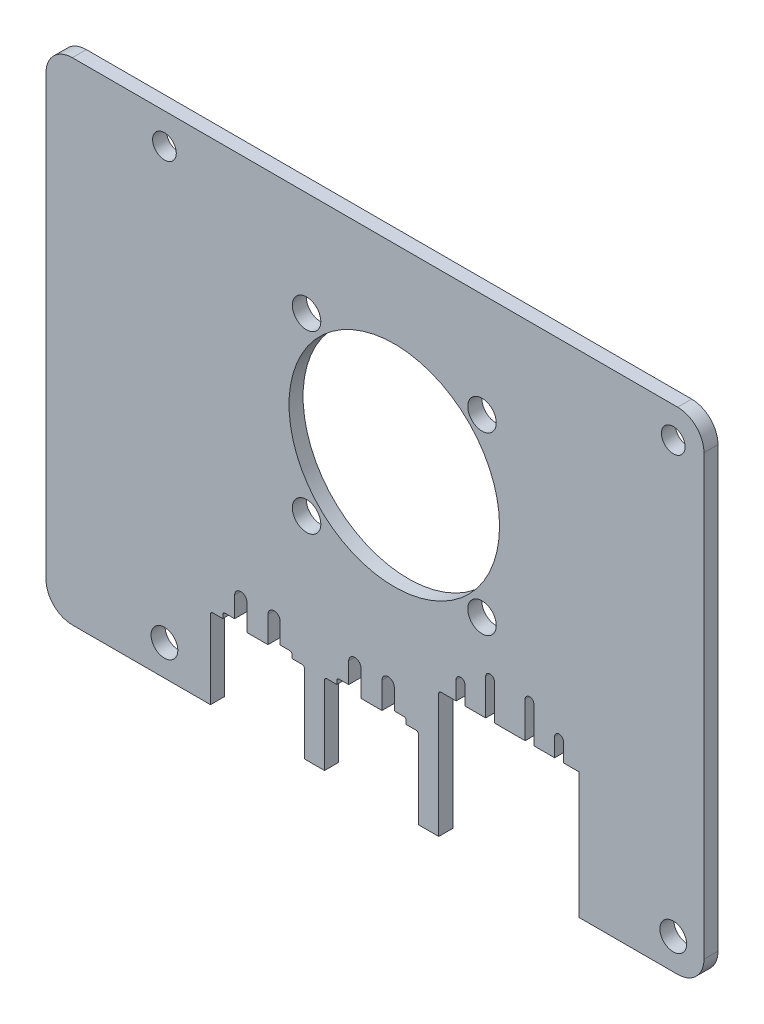
SolidWorks part; units mm, degrees
ref_plane "Front Plane" through (0, 0, 0) normal (0, 0, 1) x (1, 0, 0)
ref_plane "Top Plane" through (0, 0, 0) normal (0, 1, 0) x (1, 0, 0)
ref_plane "Right Plane" through (0, 0, 0) normal (1, 0, 0) x (0, 0, -1)
sketch "Sketch1" plane through (0, 0, 0) normal (0, 0, 1) x (1, 0, 0)
  line L0 (22.5, 25) -> (22.5, -25)
  line L1 (19, 24.5) -> (19.5, 25) construction
  line L2 (39.5, 28) -> (-39.5, 28) construction
  line L4 (42.5, -25) -> (42.5, 25)
  line L5 (39.5, 28) -> (-39.5, 28)
  line L6 (-42.5, 25) -> (-42.5, -25)
  line L7 (-39.5, -28) -> (39.5, -28)
  line L9 (19.5, 28) -> (-39.5, 28)
  line L10 (-42.5, 25) -> (-42.5, -25)
  line L11 (-39.5, -28) -> (19.5, -28)
  arc A0 (22.5, 25) -> (19.5, 28) centre (19.5, 25) ccw
  arc A1 (22.5, -25) -> (19.5, -28) centre (19.5, -25) cw
  circle A2 centre (19, 24.5) radius 1.35 construction
  circle A3 centre (-39, 24.5) radius 1.35 construction
  arc A4 (42.5, 25) -> (39.5, 28) centre (39.5, 25) ccw
  arc A5 (-39.5, 28) -> (-42.5, 25) centre (-39.5, 25) ccw
  arc A6 (-42.5, -25) -> (-39.5, -28) centre (-39.5, -25) ccw
  arc A7 (39.5, -28) -> (42.5, -25) centre (39.5, -25) ccw
  arc A9 (-39.5, 28) -> (-42.5, 25) centre (-39.5, 25) ccw
  arc A10 (-42.5, -25) -> (-39.5, -28) centre (-39.5, -25) ccw
  circle A11 centre (-39, -24.5) radius 1.524 construction
  circle A12 centre (19, -24.5) radius 1.524 construction
  circle A13 centre (-39, 24.5) radius 1.35
  circle A14 centre (-39, -24.5) radius 1.524
  circle A15 centre (19, -24.5) radius 1.524
  circle A16 centre (19, 24.5) radius 1.35
  point P18 (19, 24.5)
  dimension "D2" = 45
  dimension "D1" = 0
extrude "Boss-Extrude1" add sketch "Sketch1" along normal mid plane 1.6
sketch "Sketch2" plane through (0, 0, 0.8) normal (0, 0, 1) x (1, 0, 0)
  circle A0 centre (-2.7999, 16.11) radius 1.625
  circle A1 centre (-22.7999, 16.11) radius 1.625
  circle A2 centre (-22.7999, -3.89) radius 1.625
  circle A3 centre (-2.7999, -3.89) radius 1.625
  circle A4 centre (-12.7999, 6.11) radius 12
  point P15 (0, 0)
  dimension "D1" = 3.25
  dimension "D2" = 24
extrude "Cut-Extrude1" cut sketch "Sketch2" against normal through all
sketch "Sketch3" plane through (0, 0, 0.8) normal (0, 0, 1) x (1, 0, 0)
  line L4 (-42.5, 25) -> (-42.5, -25)
  line L5 (-39.5, -28) -> (19.5, -28)
  line L6 (22.5, -25) -> (22.5, 25)
  line L7 (19.5, 28) -> (-39.5, 28)
  line L8 (-42.5, 25) -> (-42.5, -25)
  line L9 (-39.5, -28) -> (19.5, -28)
  line L10 (22.5, -25) -> (22.5, 25)
  line L11 (19.5, 28) -> (-39.5, 28)
  arc A4 (-39.5, 28) -> (-42.5, 25) centre (-39.5, 25) ccw
  arc A5 (-42.5, -25) -> (-39.5, -28) centre (-39.5, -25) ccw
  arc A6 (19.5, -28) -> (22.5, -25) centre (19.5, -25) ccw
  arc A7 (22.5, 25) -> (19.5, 28) centre (19.5, 25) ccw
  arc A8 (-39.5, 28) -> (-42.5, 25) centre (-39.5, 25) ccw
  arc A9 (-42.5, -25) -> (-39.5, -28) centre (-39.5, -25) ccw
  arc A10 (19.5, -28) -> (22.5, -25) centre (19.5, -25) ccw
  arc A11 (22.5, 25) -> (19.5, 28) centre (19.5, 25) ccw
  point P0 (14.18, 25.89)
  point P2 (-12.7999, 6.11)
  point P7 (19, -24.5)
  point P12 (19, 24.5)
  point P15 (-39, 24.5)
  point P17 (-39, -24.5)
  point P18 (0, 0)
  point P20 (0, 0)
  point P21 (0, 0)
  point P28 (0, 0)
  point P29 (-14.5946, 28)
  dimension "D5" = 35.2999
  dimension "D2" = 3
  dimension "D3" = 59
  dimension "D4" = 53
  dimension "D6" = 34.11
  dimension "D7" = 53.89
  dimension "D8" = 8.32
  dimension "D1" = 0
sketch "Sketch4" plane through (0, 0, 0.8) normal (0, 0, 1) x (1, 0, 0)
  line L1 (-49.5, 28) -> (-39.5, 28)
  line L2 (-52.5, 25) -> (-52.5, -25)
  line L3 (-49.5, -28) -> (-39.5, -28)
  line L4 (-39.5, 28) -> (-39.5, -28)
  line L5 (-52.5, 28) -> (-39.5, -28) construction
  line L6 (-52.5, -28) -> (-39.5, 28) construction
  line L8 (19.5, 28) -> (-39.5, 28) construction
  arc A0 (-52.5, -25) -> (-49.5, -28) centre (-49.5, -25) ccw
  arc A1 (-49.5, 28) -> (-52.5, 25) centre (-49.5, 25) ccw
  arc A2 (-39.5, 28) -> (-42.5, 25) centre (-39.5, 25) ccw construction
  point P0 (-46, 0)
  point P5 (-39.5, 28)
  point P13 (0, 0)
  point P16 (-42.5, 17.6848)
  arc M14 (-39.5, 28) -> (-42.5, 25) centre (-39.5, 25) ccw
  line M15 (-42.5, 25) -> (-42.5, -25)
  arc M16 (-42.5, -25) -> (-39.5, -28) centre (-39.5, -25) ccw
  dimension "D3" = 13
extrude "Boss-Extrude2" add sketch "Sketch4" against normal up to surface (1.6 mm away) contours L1 A1 L2 A0 L3 M16 M15 M14 up to face at (-21.1749, 16.11, -0.8)
sketch "Sketch5" plane through (0, 0, 0.8) normal (0, 0, 1) x (1, 0, 0)
  line L0 (-49.5, -28) -> (19.5, -28) construction
  line L1 (-33.5, -18.8) -> (-23.3, -18.8)
  line L2 (-33.75, -19.05) -> (-33.75, -28)
  line L3 (-33.75, -28) -> (-23.05, -28)
  line L4 (-23.05, -19.05) -> (-23.05, -28)
  line L5 (-33.75, -18.8) -> (-23.05, -28) construction
  line L6 (-33.75, -28) -> (-23.05, -18.8) construction
  line L7 (-30.9, -19.8) -> (-25.9, -19.8) construction
  line L12 (-20.5, -18.8) -> (-11.925, -18.8) construction
  line L13 (-10.05, -28) -> (-20.75, -28)
  line L14 (8.4675, -28) -> (-7.7325, -28)
  line L15 (8.4675, -28) -> (8.4675, -13.875)
  line L16 (8.2175, -13.625) -> (-7.4825, -13.625)
  line L17 (-7.7325, -28) -> (-7.7325, -13.875)
  line L18 (8.4675, -28) -> (-7.7325, -13.625) construction
  line L19 (8.4675, -13.625) -> (-7.7325, -28) construction
  line L20 (-29.7, -19.8) -> (-32.1, -19.8) construction
  line L21 (-24.7, -19.8) -> (-27.1, -19.8) construction
  line L22 (-33.5, -29.5) -> (-33.5, -18.8) construction
  line L23 (-0.1325, -19) -> (0.8675, -19) construction
  line L24 (-33.5, -18.8) -> (-24.925, -18.8) construction
  line L25 (-10.05, -28) -> (-10.05, -19.05)
  line L26 (-10.3, -18.8) -> (-20.5, -18.8)
  line L27 (-20.75, -28) -> (-20.75, -19.05)
  line L28 (-10.05, -28) -> (-20.75, -18.8) construction
  line L29 (-10.05, -18.8) -> (-20.75, -28) construction
  line L30 (-30.3, -18.8) -> (-30.3, -15.8) construction
  line L31 (-31, -18.8) -> (-31, -15.8)
  line L32 (-29.6, -18.8) -> (-29.6, -15.8)
  line L33 (-29.7, -15.8) -> (-30.9, -15.8) construction
  line L34 (-29.7, -15.8) -> (-30.9, -15.8)
  line L35 (-31, -18.14) -> (-32.1, -18.14)
  line L36 (-32.35, -18.39) -> (-32.35, -18.8)
  line L37 (-30.9, -18.14) -> (-32.1, -18.14) construction
  line L38 (-30.9, -18.14) -> (-32.1, -18.14)
  line L39 (-28.4, -19.8) -> (-28.4, -23.4) construction
  line L40 (-26.5, -18.8) -> (-26.5, -15.8) construction
  line L41 (-25.8, -18.8) -> (-25.8, -15.8)
  line L42 (-27.2, -18.8) -> (-27.2, -15.8)
  line L43 (-24.45, -18.39) -> (-24.45, -18.8)
  line L44 (-25.8, -18.14) -> (-24.7, -18.14)
  line L45 (-19.35, -18.39) -> (-19.35, -18.8)
  line L46 (-18, -18.14) -> (-19.1, -18.14)
  line L47 (-12.8, -18.14) -> (-11.7, -18.14)
  line L48 (-11.45, -18.39) -> (-11.45, -18.8)
  line L49 (-17.3, -18.8) -> (-17.3, -15.8) construction
  line L50 (-18, -18.8) -> (-18, -15.8)
  line L51 (-16.6, -18.8) -> (-16.6, -15.8)
  line L52 (-13.5, -18.8) -> (-13.5, -15.8) construction
  line L53 (-12.8, -18.8) -> (-12.8, -15.8)
  line L54 (-14.2, -18.8) -> (-14.2, -15.8)
  line L55 (8.235, -29.25) -> (8.235, -13.625) construction
  line L56 (8.235, -13.625) -> (-4.3964, -13.625) construction
  line L57 (-7.4268, -29.25) -> (-7.4268, -13.875) construction
  line L58 (8.235, -29.25) -> (8.235, -13.625)
  line L59 (8.235, -13.625) -> (-4.3964, -13.625)
  line L60 (-7.4268, -29.25) -> (-7.4268, -13.875)
  line L61 (-5.2475, -13.625) -> (-5.2475, -11.525) construction
  line L62 (-5.7475, -13.625) -> (-5.7475, -11.525)
  line L63 (-4.7475, -13.625) -> (-4.7475, -11.525)
  line L64 (-1.8825, -13.625) -> (-1.8825, -9.525) construction
  line L65 (-2.3825, -13.625) -> (-2.3825, -9.525)
  line L66 (-1.3825, -13.625) -> (-1.3825, -9.525)
  line L67 (0.3675, -20.8125) -> (0.3675, -13.625) construction
  line L68 (5.9825, -13.625) -> (5.9825, -11.525) construction
  line L69 (6.4825, -13.625) -> (6.4825, -11.525)
  line L70 (5.4825, -13.625) -> (5.4825, -11.525)
  line L71 (2.6175, -13.625) -> (2.6175, -9.525) construction
  line L72 (3.1175, -13.625) -> (3.1175, -9.525)
  line L73 (2.1175, -13.625) -> (2.1175, -9.525)
  line L75 (-2.3825, -11.575) -> (-4.7475, -11.575) construction
  line L76 (-5.398, -11.623) -> (-5.398, -20)
  line L77 (-1.734, -20) -> (-1.734, -9.623)
  line L78 (-1.734, -20) -> (-1.734, -9.623)
  line L79 (-5.398, -11.623) -> (-5.398, -20)
  line L82 (-33.75, -28) -> (-33.75, -29.5)
  line L83 (-33.5, -29.75) -> (-23.3, -29.75)
  line L84 (-23.05, -29.5) -> (-23.05, -28)
  line L85 (-33.5, -29.5) -> (-24.925, -29.5) construction
  line L86 (-20.75, -28) -> (-20.75, -28.2)
  line L87 (-20.5, -28.45) -> (-10.3, -28.45)
  line L88 (-10.05, -28.2) -> (-10.05, -28)
  line L89 (-14.8861, -28.2) -> (-12.9, -28.2) construction
  line L90 (-7.7325, -28) -> (-7.7325, -29.5)
  line L91 (-7.4825, -29.75) -> (8.2175, -29.75)
  line L92 (8.4675, -29.5) -> (8.4675, -28)
  line L94 (-0.1325, -19) -> (0.8675, -19)
  arc A0 (-31, -18.8) -> (-29.6, -18.8) centre (-30.3, -18.8) ccw
  arc A1 (-29.6, -15.8) -> (-31, -15.8) centre (-30.3, -15.8) ccw
  arc A2 (-32.35, -18.39) -> (-32.1, -18.14) centre (-32.1, -18.39) cw
  arc A3 (-25.8, -18.8) -> (-27.2, -18.8) centre (-26.5, -18.8) cw
  arc A4 (-27.2, -15.8) -> (-25.8, -15.8) centre (-26.5, -15.8) cw
  arc A5 (-24.45, -18.39) -> (-24.7, -18.14) centre (-24.7, -18.39) ccw
  arc A6 (-10.05, -19.05) -> (-10.3, -18.8) centre (-10.3, -19.05) ccw
  arc A7 (-20.5, -18.8) -> (-20.75, -19.05) centre (-20.5, -19.05) ccw
  arc A8 (-23.3, -18.8) -> (-23.05, -19.05) centre (-23.3, -19.05) cw
  arc A9 (-33.5, -18.8) -> (-33.75, -19.05) centre (-33.5, -19.05) ccw
  arc A10 (-19.35, -18.39) -> (-19.1, -18.14) centre (-19.1, -18.39) cw
  arc A11 (-11.45, -18.39) -> (-11.7, -18.14) centre (-11.7, -18.39) ccw
  arc A12 (-18, -18.8) -> (-16.6, -18.8) centre (-17.3, -18.8) ccw
  arc A13 (-16.6, -15.8) -> (-18, -15.8) centre (-17.3, -15.8) ccw
  arc A14 (-12.8, -18.8) -> (-14.2, -18.8) centre (-13.5, -18.8) cw
  arc A15 (-14.2, -15.8) -> (-12.8, -15.8) centre (-13.5, -15.8) cw
  arc A16 (-5.7475, -13.625) -> (-4.7475, -13.625) centre (-5.2475, -13.625) ccw
  arc A17 (-4.7475, -11.525) -> (-5.7475, -11.525) centre (-5.2475, -11.525) ccw
  arc A18 (-2.3825, -13.625) -> (-1.3825, -13.625) centre (-1.8825, -13.625) ccw
  arc A19 (-1.3825, -9.525) -> (-2.3825, -9.525) centre (-1.8825, -9.525) ccw
  arc A20 (6.4825, -13.625) -> (5.4825, -13.625) centre (5.9825, -13.625) cw
  arc A21 (5.4825, -11.525) -> (6.4825, -11.525) centre (5.9825, -11.525) cw
  arc A22 (3.1175, -13.625) -> (2.1175, -13.625) centre (2.6175, -13.625) cw
  arc A23 (2.1175, -9.525) -> (3.1175, -9.525) centre (2.6175, -9.525) cw
  arc A24 (8.4675, -13.875) -> (8.2175, -13.625) centre (8.2175, -13.875) ccw
  arc A25 (-7.4825, -13.625) -> (-7.7325, -13.875) centre (-7.4825, -13.875) ccw
  arc A26 (-23.3, -29.75) -> (-23.05, -29.5) centre (-23.3, -29.5) ccw
  arc A27 (-33.75, -29.5) -> (-33.5, -29.75) centre (-33.5, -29.5) ccw
  arc A28 (-10.3, -28.45) -> (-10.05, -28.2) centre (-10.3, -28.2) ccw
  arc A29 (-20.75, -28.2) -> (-20.5, -28.45) centre (-20.5, -28.2) ccw
  arc A30 (8.2175, -29.75) -> (8.4675, -29.5) centre (8.2175, -29.5) ccw
  arc A31 (-7.7325, -29.5) -> (-7.4825, -29.75) centre (-7.4825, -29.5) ccw
  point P0 (-28.4, -23.4)
  point P8 (0.3675, -20.8125)
  point P9 (-15.4, -23.4)
  point P21 (-28.4, -19.8)
  point P32 (-30.3, -17.3)
  point P49 (-26.5, -17.3)
  point P71 (-5.2475, -12.575)
  point P75 (-17.3, -17.3)
  point P87 (-13.5, -17.3)
  point P107 (-1.8825, -11.575)
  point P118 (5.9825, -12.575)
  point P125 (2.6175, -11.575)
  point P136 (-3.565, -11.575)
  point P171 (0.3675, -19)
  dimension "D5" = 0.25
  dimension "D6" = 0.25
  dimension "D11" = 0.5
  dimension "D14" = 0.25
  dimension "D15" = 0.25
  dimension "D18" = 0.25
  dimension "D19" = 0.25
  dimension "D1" = 0.25
  dimension "D2" = 13
  dimension "D3" = 0.1
  dimension "D4" = 0.1
  dimension "D8" = 13
  dimension "D9" = 16.2
  dimension "D10" = 16.125
  dimension "D12" = 2.25
  dimension "D13" = 5.615
  dimension "D16" = 0.25
  dimension "D17" = 0.25
  dimension "D20" = 2.1
  dimension "D21" = 10.95
  dimension "D22" = 7.9
  dimension "D23" = 5.2
  dimension "D24" = 2.4
  dimension "D25" = 9.65
  dimension "D26" = 4.1
  dimension "D27" = 6.115
  dimension "D28" = 5.615
  dimension "D29" = 2.25
  dimension "D30" = 2.365
  dimension "D31" = 5.115
  dimension "D32" = 2.75
  dimension "D33" = 3.9325
  dimension "D7" = 2
extrude "Cut-Extrude2" cut sketch "Sketch5" against normal through all
sketch "Sketch6" plane through (0, 0, 0.8) normal (0, 0, 1) x (1, 0, 0)
  line L0 (2.1175, -13.625) -> (-1.3825, -13.625) construction
  line L1 (-14.2, -18.8) -> (-16.6, -18.8) construction
  line L2 (-29.6, -18.8) -> (-27.2, -18.8) construction
  line L3 (22.5, -25) -> (22.5, 25) construction
  line L4 (19.5, 28) -> (-49.5, 28) construction
  line L5 (8.235, -28) -> (19.5, -28) construction
  line L6 (-52.5, 25) -> (-52.5, -25) construction
  line L7 (-52.5, 25) -> (-52.5, -25)
  line L8 (22.5, -25) -> (22.5, 25)
  line L9 (-47.5024, 3.9375) -> (-47.5024, -3.9295) construction
  line L10 (-49.5, -28) -> (-33.75, -28) construction
  point P0 (0.3675, -13.625)
  point P1 (-15.4, -18.8)
  point P4 (-28.4, -18.8)
  point P21 (-47.5024, 0.004)
  point P24 (0, 0)
  dimension "D1" = 22.1325
  dimension "D2" = 37.9
  dimension "D3" = 50.9
  dimension "D4" = 41.625
  dimension "D5" = 46.8
  dimension "D6" = 9.2
  dimension "D7" = 14.375
  dimension "D8" = 75
  dimension "D9" = 70.0024
  dimension "D10" = 28.004
